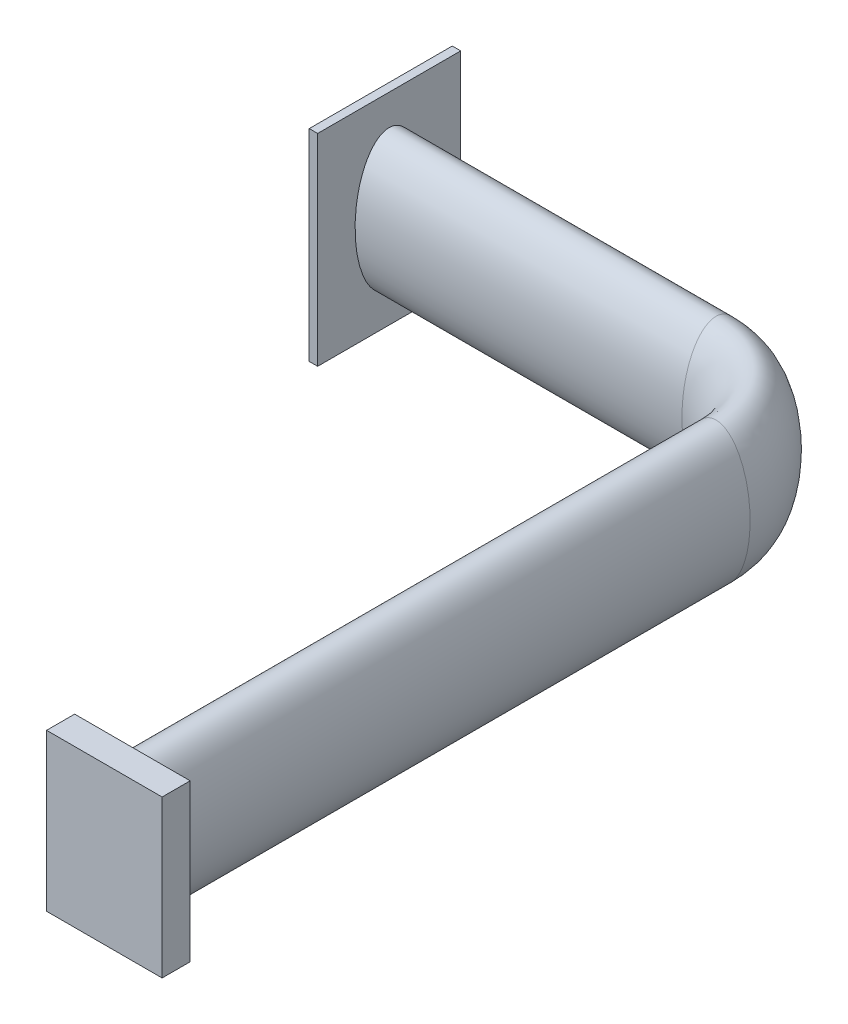
SolidWorks part; units mm, degrees
ref_plane "Front Plane" through (0, 0, 0) normal (0, 0, 1) x (1, 0, 0)
ref_plane "Top Plane" through (0, 0, 0) normal (0, 1, 0) x (1, 0, 0)
ref_plane "Right Plane" through (0, 0, 0) normal (1, 0, 0) x (0, 0, -1)
sketch "Sketch1" plane through (0, 0, 0) normal (0, 0, 1) x (1, 0, 0)
  ellipse E0 centre (0, 0) end of major axis (0, 63.5) minor radius 30.8761
  dimension "D1" = 127
sketch "Sketch2" plane through (0, 0, 0) normal (0, 1, 0) x (1, 0, 0)
  line L0 (0, 0) -> (0, 528.32)
  line L1 (-81.28, 609.6) -> (-377.173, 609.6)
  arc A0 (0, 528.32) -> (-81.28, 609.6) centre (-81.28, 528.32) ccw
  point P6 (0, 609.6)
  dimension "D2" = 81.28
  dimension "D1" = 609.6
sweep "Sweep1" add profiles "Sketch1" path "Sketch2"
shell "Shell1" thickness 4.4958
sketch "Sketch3" plane through (0, 0, 0) normal (0, 0, 1) x (1, 0, 0)
  line L1 (-52.2895, -70.9489) -> (52.2895, -70.9489)
  line L2 (-52.2895, -70.9489) -> (-52.2895, 70.9489)
  line L3 (-52.2895, 70.9489) -> (52.2895, 70.9489)
  line L4 (52.2895, -70.9489) -> (52.2895, 70.9489)
  line L5 (-52.2895, -70.9489) -> (52.2895, 70.9489) construction
  line L6 (-52.2895, 70.9489) -> (52.2895, -70.9489) construction
  point P0 (0, 0)
extrude "Boss-Extrude1" add sketch "Sketch3" along normal blind 25.4
sketch "Sketch4" plane through (-377.173, 0, 0) normal (-1, 0, 0) x (0, 0, 1)
  line L1 (-674.3373, -91.2952) -> (-544.8627, -91.2952)
  line L2 (-674.3373, -91.2952) -> (-674.3373, 91.2952)
  line L3 (-674.3373, 91.2952) -> (-544.8627, 91.2952)
  line L4 (-544.8627, -91.2952) -> (-544.8627, 91.2952)
  line L5 (-674.3373, -91.2952) -> (-544.8627, 91.2952) construction
  line L6 (-674.3373, 91.2952) -> (-544.8627, -91.2952) construction
  point P0 (-609.6, 0)
extrude "Boss-Extrude2" add sketch "Sketch4" along normal blind 7.62
